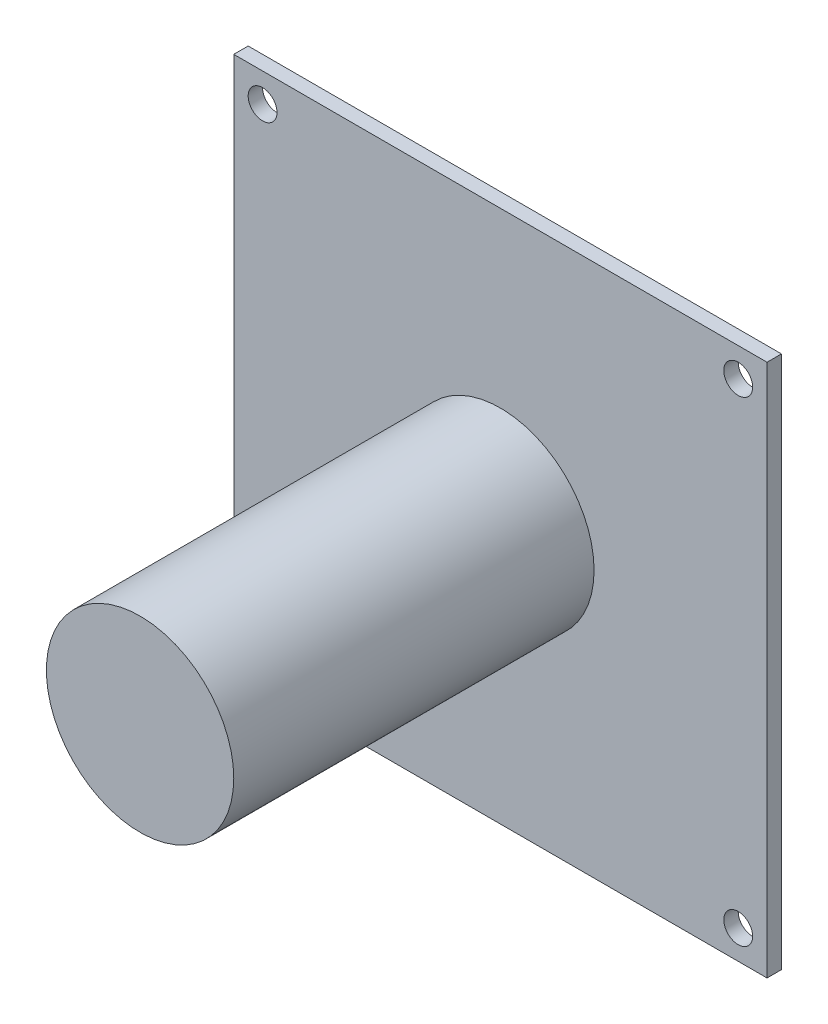
SolidWorks part; units mm, degrees
ref_plane "前视基准面" through (0, 0, 0) normal (0, 0, 1) x (1, 0, 0)
ref_plane "上视基准面" through (0, 0, 0) normal (0, 1, 0) x (1, 0, 0)
ref_plane "右视基准面" through (0, 0, 0) normal (1, 0, 0) x (0, 0, -1)
other "Configuration Table"
sketch "Measured_PCB_37x37" plane through (0, 0, 0) normal (0, 0, 1) x (1, 0, 0)
  line L1 (-18.5, -18.5) -> (18.5, -18.5)
  line L2 (-18.5, -18.5) -> (-18.5, 18.5)
  line L3 (-18.5, 18.5) -> (18.5, 18.5)
  line L4 (18.5, -18.5) -> (18.5, 18.5)
extrude "PCB_visual_thickness_1mm_UNMEASURED" add sketch "Measured_PCB_37x37" along normal blind 1
sketch "Lens_OD13_center_PROVISIONAL" plane through (0, 0, 0) normal (0, 0, 1) x (1, 0, 0)
  circle A0 centre (0, 0) radius 6.5
extrude "Lens_height25_from_PCB_front" add sketch "Lens_OD13_center_PROVISIONAL" along normal blind 25 from offset 1
sketch "Hole_centers33_PROVISIONAL" plane through (0, 0, 0) normal (0, 0, 1) x (1, 0, 0)
  circle A0 centre (-16.5, -16.5) radius 1
  circle A1 centre (-16.5, 16.5) radius 1
  circle A2 centre (16.5, -16.5) radius 1
  circle A3 centre (16.5, 16.5) radius 1
extrude "Four_measured_D2_holes_PROVISIONAL_locations" cut sketch "Hole_centers33_PROVISIONAL" against normal through all and the other way through all
